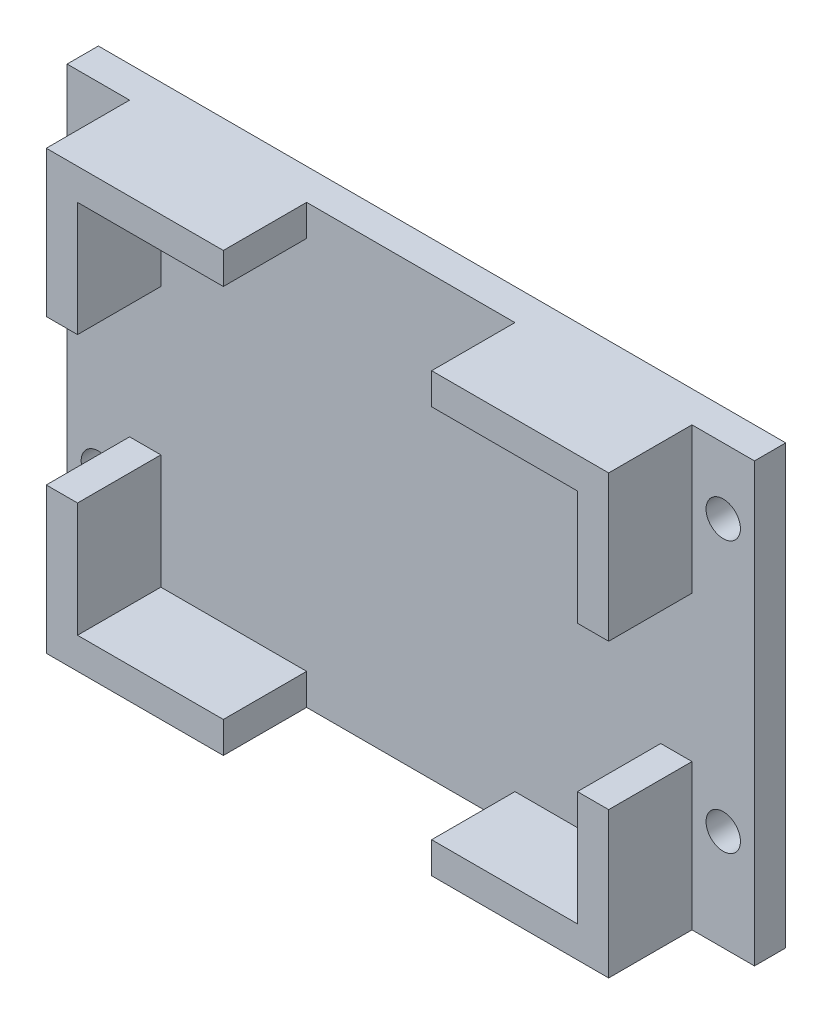
SolidWorks part; units mm, degrees
ref_plane "前视基准面" through (0, 0, 0) normal (0, 0, 1) x (1, 0, 0)
ref_plane "上视基准面" through (0, 0, 0) normal (0, 1, 0) x (1, 0, 0)
ref_plane "右视基准面" through (0, 0, 0) normal (1, 0, 0) x (0, 0, -1)
sketch "草图1" plane through (0, 0, 0) normal (0, 0, 1) x (1, 0, 0)
  line L0 (0, 0) -> (0, 21)
  line L1 (-27, 21) -> (27, 21)
  line L2 (-27, 21) -> (-27, -21)
  line L3 (-27, -21) -> (27, -21)
  line L4 (27, 21) -> (27, -21)
  line L5 (-27, 21) -> (27, -21) construction
  line L6 (-27, -21) -> (27, 21) construction
  line L7 (-24, 18) -> (24, 18)
  line L8 (-24, 18) -> (-24, -18)
  line L9 (-24, -18) -> (24, -18)
  line L10 (24, 18) -> (24, -18)
  line L11 (-24, 18) -> (24, -18) construction
  line L12 (-24, -18) -> (24, 18) construction
  line L13 (27, 21) -> (33, 21)
  line L14 (27, 21) -> (27, -21)
  line L15 (27, -21) -> (33, -21)
  line L16 (33, 21) -> (33, -21)
  line L17 (-27, 21) -> (-33, 21)
  line L18 (-27, 21) -> (-27, -21)
  line L19 (-27, -21) -> (-33, -21)
  line L20 (-33, 21) -> (-33, -21)
  line L21 (-30, 21) -> (-30, 14.6832)
  line L22 (-30, 14.6832) -> (-30, -11.3168)
  circle A0 centre (-30, 14.6832) radius 1.65
  circle A1 centre (-30, -11.3168) radius 1.65
  circle A2 centre (30, -11.3168) radius 1.65
  circle A3 centre (30, 14.6832) radius 1.65
  point P0 (0, 0)
  point P6 (0, 0)
  dimension "D1" = 42
  dimension "D3" = 3.3
  dimension "D4" = 3.3
  dimension "D2" = 6
extrude "凸台-拉伸3" add sketch "草图1" along normal blind 3
sketch "草图3" plane through (0, 0, 3) normal (0, 0, 1) x (1, 0, 0)
  line L1 (-24, 18) -> (24, 18)
  line L2 (-24, 18) -> (-24, -18)
  line L3 (-24, -18) -> (24, -18)
  line L4 (24, 18) -> (24, -18)
  line L5 (-24, 18) -> (24, -18) construction
  line L6 (-24, -18) -> (24, 18) construction
  line L7 (-27, 21) -> (27, 21)
  line L8 (-27, 21) -> (-27, -21)
  line L9 (-27, -21) -> (27, -21)
  line L10 (27, 21) -> (27, -21)
  line L11 (-27, 21) -> (27, -21) construction
  line L12 (-27, -21) -> (27, 21) construction
  point P0 (0, 0)
  point P6 (0, 0)
extrude "凸台-拉伸4" add sketch "草图3" along normal blind 8
sketch "草图4" plane through (0, -21, 0) normal (0, -1, 0) x (1, 0, 0)
  line L0 (-10, 11) -> (-10, 3)
  line L1 (-27, 11) -> (27, 11) construction
  line L2 (-10, 3) -> (10, 3)
  line L3 (10, 3) -> (10, 11)
  line L4 (0, 0) -> (0, 31.1009) construction
  line L5 (33, 0) -> (-33, 0) construction
  line L6 (33, 3) -> (27, 3) construction
  dimension "D1" = 20
extrude "切除-拉伸1" cut sketch "草图4" against normal through all and the other way through all
sketch "草图5" plane through (-27, 0, 0) normal (-1, 0, 0) x (0, 0, 1)
  line L0 (0, 0) -> (26.7504, 0) construction
  line L1 (11, 7) -> (3, 7)
  line L2 (11, 21) -> (11, -21) construction
  line L3 (3, 21) -> (3, -21) construction
  line L4 (3, 7) -> (3, -7)
  line L5 (3, 21) -> (3, -21) construction
  line L6 (3, -7) -> (11, -7)
  line L7 (11, 7) -> (11, -7)
  dimension "D1" = 14
extrude "切除-拉伸2" cut sketch "草图5" against normal through all
